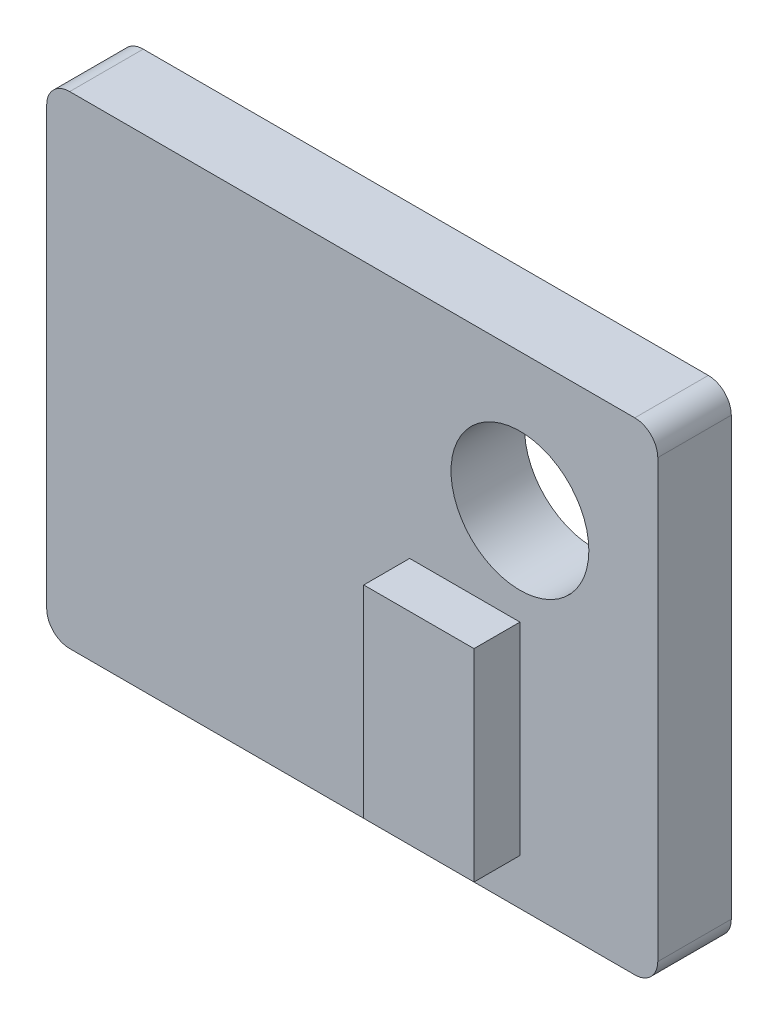
SolidWorks part; units mm, degrees
ref_plane "Front Plane" through (0, 0, 0) normal (0, 0, 1) x (1, 0, 0)
ref_plane "Top Plane" through (0, 0, 0) normal (0, 1, 0) x (1, 0, 0)
ref_plane "Right Plane" through (0, 0, 0) normal (1, 0, 0) x (0, 0, -1)
sketch "Sketch1" plane through (0, 0, 0) normal (0, 0, 1) x (1, 0, 0)
  line L1 (6.65, -5.25) -> (-6.65, -5.25)
  line L2 (6.65, -5.25) -> (6.65, 5.25)
  line L3 (6.65, 5.25) -> (-6.65, 5.25)
  line L4 (-6.65, -5.25) -> (-6.65, 5.25)
  line L5 (6.65, -5.25) -> (-6.65, 5.25) construction
  line L6 (6.65, 5.25) -> (-6.65, -5.25) construction
  point P0 (0, 0)
  dimension "D1" = 13.3
  dimension "D2" = 10.5
extrude "Boss-Extrude1" add sketch "Sketch1" along normal blind 1.6
sketch "Sketch2" plane through (0, 0, 1.6) normal (0, 0, 1) x (1, 0, 0)
  line L0 (6.65, -5.25) -> (6.65, 5.25) construction
  line L1 (6.65, 5.25) -> (-6.65, 5.25) construction
  circle A0 centre (3.65, 2.25) radius 1.5
  dimension "D1" = 3
  dimension "D2" = 3
  dimension "D3" = 3
extrude "Cut-Extrude1" cut sketch "Sketch2" against normal blind 1.6
sketch "Sketch3" plane through (0, 0, 1.6) normal (0, 0, 1) x (1, 0, 0)
  line L0 (6.65, -5.25) -> (6.65, 5.25) construction
  line L1 (1.25, 0.15) -> (3.65, 0.15)
  line L2 (1.25, 0.15) -> (1.25, -4.25)
  line L3 (1.25, -4.25) -> (3.65, -4.25)
  line L4 (3.65, 0.15) -> (3.65, -4.25)
  line L5 (1.25, 0.15) -> (3.65, -4.25) construction
  line L6 (1.25, -4.25) -> (3.65, 0.15) construction
  line L7 (-6.65, -5.25) -> (6.65, -5.25) construction
  point P0 (2.45, -2.05)
  dimension "D1" = 2.4
  dimension "D2" = 4.4
  dimension "D3" = 3
  dimension "D4" = 1
extrude "Boss-Extrude2" add sketch "Sketch3" along normal blind 1
fillet "Fillet1" radius 0.5 4 edges at (-6.65, -5.25, 0.8) (-6.65, 5.25, 0.8) (6.65, -5.25, 0.8) (6.65, 5.25, 0.8)
